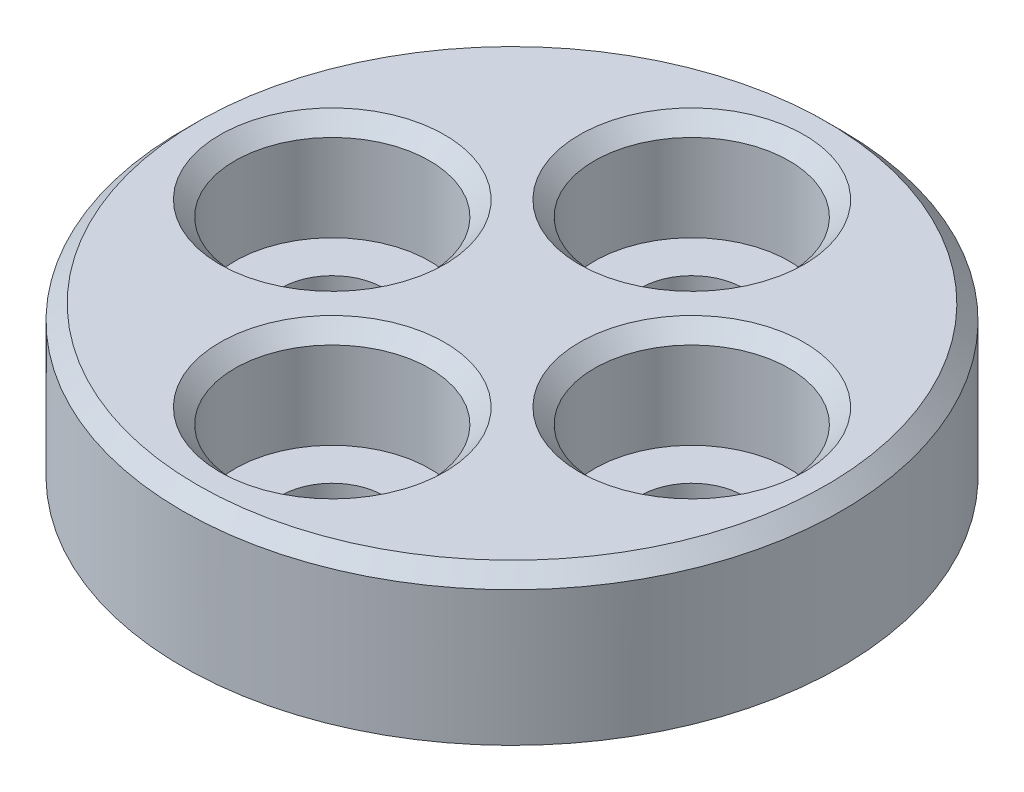
SolidWorks part; units mm, degrees
ref_plane "Front Plane" through (0, 0, 0) normal (0, 0, 1) x (1, 0, 0)
ref_plane "Top Plane" through (0, 0, 0) normal (0, 1, 0) x (1, 0, 0)
ref_plane "Right Plane" through (0, 0, 0) normal (1, 0, 0) x (0, 0, -1)
sketch "Sketch1" plane through (0, 0, 0) normal (0, 0, 1) x (1, 0, 0)
  line L0 (0, 0) -> (11, 0)
  line L1 (11, 0) -> (11, 5)
  line L2 (11, 5) -> (0, 5)
  line L5 (0, 5) -> (0, 0)
  line L6 (0, 0) -> (0, 3.1818) construction
  point P5 (0, 0.7518)
  point P6 (0, 0)
  dimension "D1" = 5
  dimension "D2" = 22
revolve "Revolve1" add sketch "Sketch1" angle 360 about L6
hole_wizard "CBORE for M3 Hex Socket Head Cap Screw1" positions "Sketch2" profile "Sketch3" counterbore size "M3" standard "DIN"
sketch "Sketch2" plane through (0, 5, 0) normal (0, 1, 0) x (1, 0, 0)
  circle A0 centre (0, 0) radius 6
  point P4 (0, 6)
  point P6 (6, 0)
  point P8 (0, -6)
  point P10 (-6, 0)
  point P13 (-6, 0)
  dimension "D1" = 12
sketch "Sketch3" plane through (-6, 5, 0) normal (1, 0, 0) x (0, 0, 1)
  line L0 (0, 0) -> (0, 12.0215)
  line L1 (0, 12.0215) -> (1.7, 11)
  line L2 (1.7, 11) -> (1.7, 3.4)
  line L3 (1.7, 3.4) -> (3.25, 3.4)
  line L4 (3.25, 3.4) -> (3.25, 0)
  line L5 (3.25, 0) -> (0, 0)
  line L10 (0, 12.0215) -> (-1.7, 11) construction
  line L11 (0, -6.35) -> (0, 107.95) construction
  dimension "Hole Dia." = 3.4
  dimension "Hole Depth" = 11
  dimension "C'Bore Dia." = 6.5
  dimension "C'Bore Depth" = 3.4
  dimension "Drill Angle" = 118
chamfer "Chamfer1" distance 0.5 angle 45 9 edges at (0, 5, -11) (-6, 5, 3.25) (0, 5, 9.25) (6, 5, 3.25) (0, 5, -2.75) (6, 0, -1.7) (0, 0, 4.3) (-6, 0, -1.7) (0, 0, -7.7)
